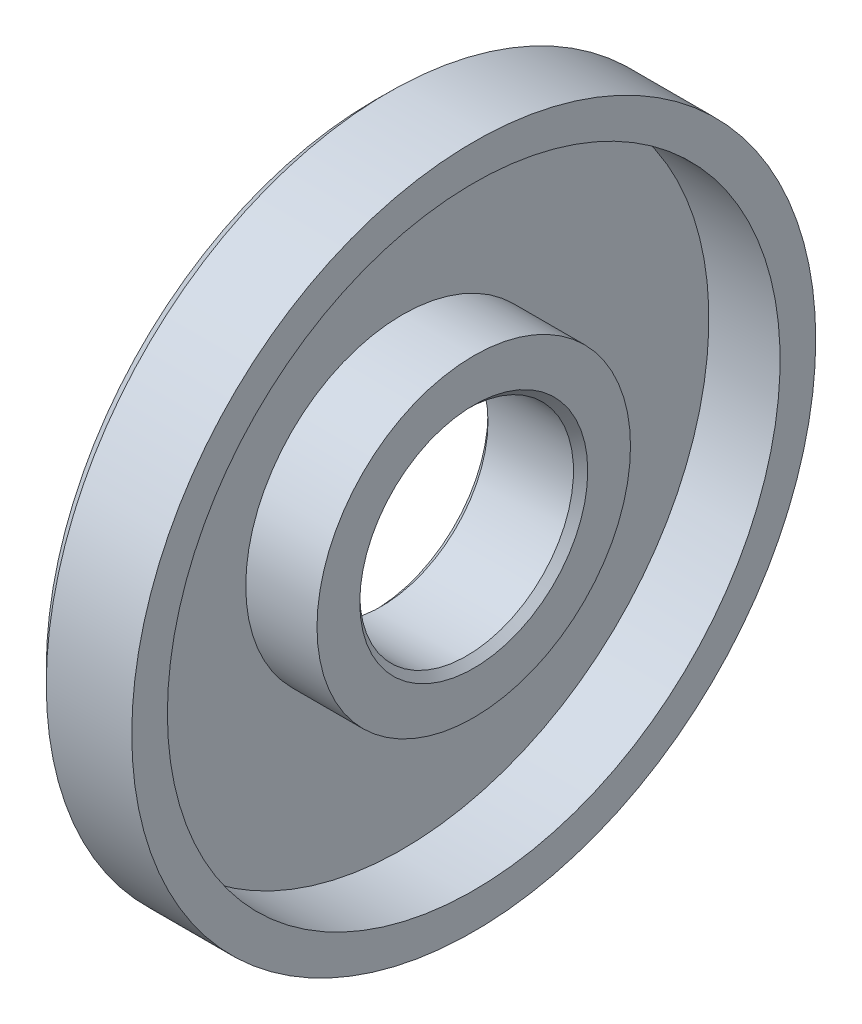
SolidWorks part; units mm, degrees
material "Сталь 3 ГОСТ 535-88"
ref_plane "Спереди" through (0, 0, 0) normal (0, 0, 1) x (1, 0, 0)
ref_plane "Сверху" through (0, 0, 0) normal (0, 1, 0) x (1, 0, 0)
ref_plane "Справа" through (0, 0, 0) normal (1, 0, 0) x (0, 0, -1)
sketch "Эскиз1" plane through (0, 0, 0) normal (0, 0, 1) x (1, 0, 0)
  line L0 (7, 21.5) -> (2, 21.5)
  line L1 (0, 0) -> (7, 0) construction
  line L2 (0, 7.5) -> (0, 24)
  line L3 (0, 24) -> (7, 24)
  line L11 (0, 7.5) -> (7, 7.5)
  line L16 (2, 11) -> (2, 21.5)
  line L17 (7, 11) -> (2, 11)
  line L19 (7, 7.5) -> (7, 11)
  line L20 (7, 21.5) -> (7, 24)
  dimension "D1" = 7
  dimension "D2" = 43
  dimension "D3" = 15
  dimension "D4" = 3.5
  dimension "D5" = 2.5
  dimension "D6" = 2
  dimension "D7" = 7
revolve "Повернуть1" add sketch "Эскиз1" angle 360 about L1
cosmetic thread "Условное изображение резьбы1" parameters "D2"=16
chamfer "Фаска1" distance 1 angle 45 1 edges at (0, 0, 24)
chamfer "Фаска2" distance 0.5 angle 45 2 edges at (0, 0, 7.5) (7, 0, 7.5)
